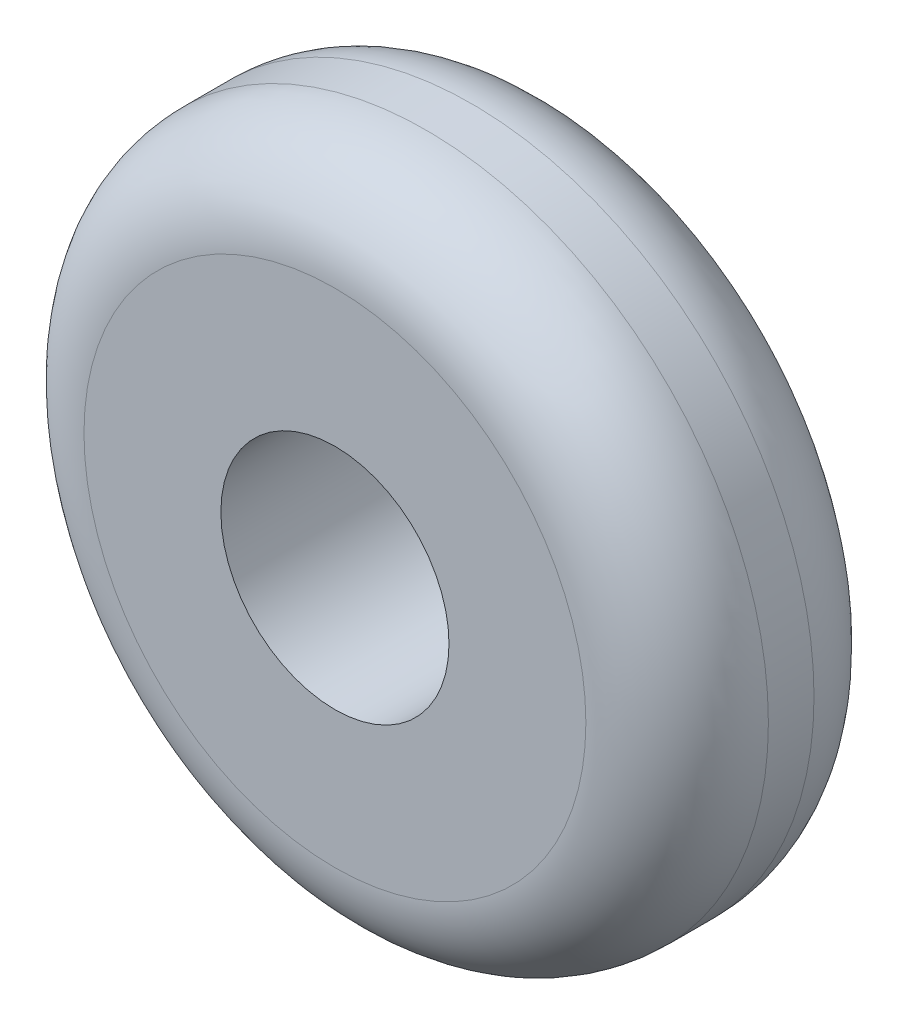
SolidWorks part; units mm, degrees
ref_plane "Front Plane" through (0, 0, 0) normal (0, 0, 1) x (1, 0, 0)
ref_plane "Top Plane" through (0, 0, 0) normal (0, 1, 0) x (1, 0, 0)
ref_plane "Right Plane" through (0, 0, 0) normal (1, 0, 0) x (0, 0, -1)
sketch "Sketch1" plane through (0, 0, 0) normal (0, 0, 1) x (1, 0, 0)
  circle A0 centre (0, 0) radius 2.5
  circle A1 centre (0, 0) radius 7.5
  dimension "D1" = 5
  dimension "D2" = 15
extrude "Boss-Extrude1" add sketch "Sketch1" along normal blind 5
fillet "Fillet6" radius 2 2 edges at (7.5, 0, 5) (7.5, 0, 0)
